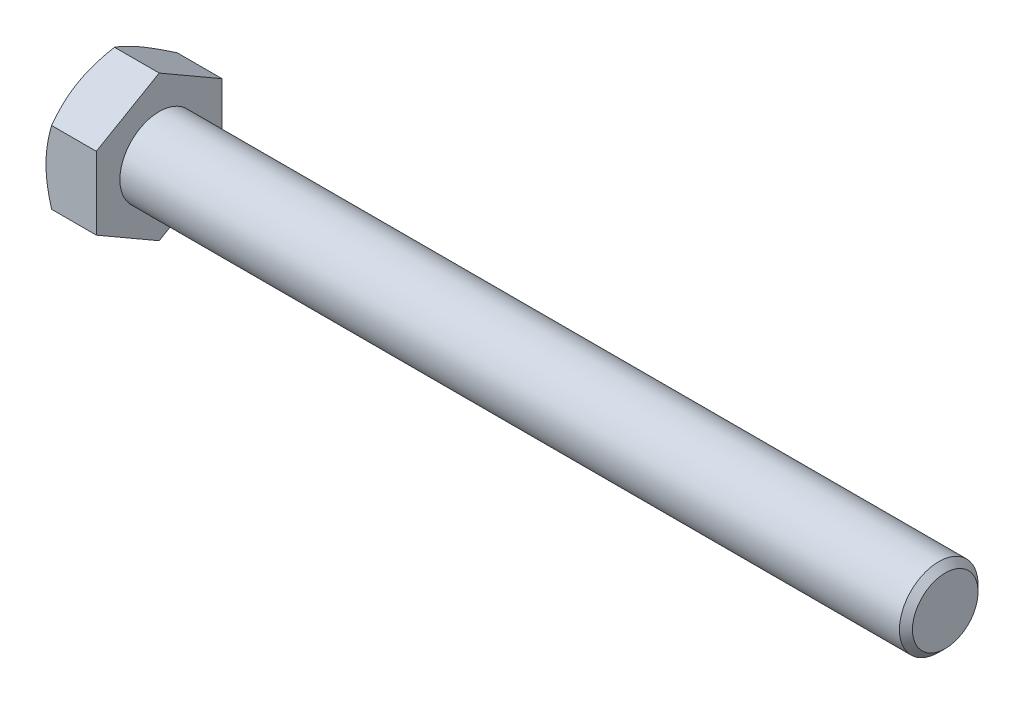
SolidWorks part; units mm, degrees
extrude "BaseHead" add sketch "Sketch1" along normal blind 6.4
sketch "Sketch1" plane through (0, 0, 0) normal (1, 0, 0) x (0, 0, -1)
  line L0 (8, 4.6188) -> (8, -4.6188)
  line L1 (-8, 4.6188) -> (-8, -4.6188)
  line L2 (8, -4.6188) -> (0, -9.2376)
  line L3 (0, -9.2376) -> (-8, -4.6188)
  line L4 (8, 4.6188) -> (0, 9.2376)
  line L5 (0, 9.2376) -> (-8, 4.6188)
  dimension "Width_flats" = 16
  dimension "D2" = 120
  dimension "D3" = 8
  dimension "D4" = 8
  dimension "D5" = 8
ref_plane "Plane1" through (0, 0, 0) normal (0, 0, 1) x (1, 0, 0)
ref_plane "Plane2" through (0, 0, 0) normal (0, 1, 0) x (1, 0, 0)
ref_plane "Plane3" through (0, 0, 0) normal (1, 0, 0) x (0, 0, -1)
sketch "BodySke" plane through (0, 0, 0) normal (0, 0, 1) x (1, 0, 0)
  line L1 (0, 0) -> (106.4, 0)
  line L2 (0, 0) -> (0, 5)
  line L4 (106.4, 0) -> (106.4, 4.172)
  line L5 (6.4, 9.2376) -> (6.4, 4.6188) construction
  line L6 (106.4, 4.172) -> (105.572, 5)
  line L7 (0, 0) -> (110.49, 0) construction
  line L8 (106.4, -4.172) -> (105.572, -5) construction
  line L9 (0, 4.6188) -> (0, -4.6188) construction
  line L10 (7.9, 15.24) -> (7.9, -1.27) construction
  line L11 (80.4, 15.24) -> (80.4, -1.27) construction
  line L12 (6.4, 4.6188) -> (6.4, -4.6188) construction
  line L15 (0, 5) -> (105.572, 5)
  dimension "Body_ch_ang" = 45
  dimension "Minor_dia" = 8.344
  dimension "Diameter" = 10
revolve "BaseBody" add sketch "BodySke" angle 360 about L7
cosmetic thread "ThreadCosmetic" parameters "Thread_length"=26, "Thread_minor"=8.344
fillet "HeadFillet" [suppressed] radius 0.4
sketch "Sketch3" plane through (0, 0, 0) normal (0, 0, 1) x (1, 0, 0)
  line L0 (0, 8) -> (3.6013, 14.2376)
  line L1 (0, 9.2376) -> (0, 4.6188) construction
  line L2 (3.6013, 14.2376) -> (3.6013, 19.2376)
  line L3 (3.6013, 19.2376) -> (-10, 19.2376)
  line L4 (-10, 19.2376) -> (-10, 8)
  line L5 (-10, 8) -> (0, 8)
  line L6 (0, 0) -> (99.06, 0) construction
  line L7 (6.4, 9.2376) -> (0, 9.2376) construction
  dimension "D1" = 8
  dimension "D2" = 5
  dimension "D3" = 10
  dimension "D4" = 5
  dimension "Head_ch_ang" = 30
revolve "HeadChamfer" cut sketch "Sketch3" angle 360 about L6
sketch "ThdSchSke" plane through (0, 0, 0) normal (0, 0, 1) x (1, 0, 0)
  line L0 (80.4, -4.172) -> (79.8202, -5)
  line L1 (80.4, -4.172) -> (80.9798, -5)
  line L2 (80.9798, -5) -> (80.9798, -6.25)
  line L3 (-3.175, 0) -> (5.1513, 0) construction
  line L5 (80.9798, -6.25) -> (79.8202, -6.25)
  line L6 (79.8202, -6.25) -> (79.8202, -5)
  dimension "Thread_minor" = 8.344
  dimension "Diameter" = 10
  dimension "Start" = 80.4
revolve "ThreadSchematic" [suppressed] cut sketch "ThdSchSke" angle 360 about L3
pattern_linear "ThdSchPat" [suppressed]
equation "\"D3@Sketch1\" = \"Width_flats@Sketch1\" / 2"
equation "\"D4@Sketch1\" = \"D3@Sketch1\""
equation "\"D5@Sketch1\" = \"D4@Sketch1\""
equation "\"Thread_minor@ThreadCosmetic\" = \"Minor_dia@BodySke\""
equation "\"D1@Sketch3\" = \"Width_flats@Sketch1\" / 2"
equation "\"Thread_length@ThreadCosmetic\" = ((sgn( (\"Length@BodySke\" - \"Advance@BodySke\" ) - \"Thread_nom@BodySke\" )-1)*( (\"Length@BodySke\" - \"Advance@BodySke\" ) - \"Thread_nom@BodySke\" ))/-2+ \"Thread_nom@BodySke\""
equation "\"Thread_minor@ThdSchSke\" = \"Minor_dia@BodySke\""
equation "\"Diameter@ThdSchSke\" = \"Diameter@BodySke\""
equation "\"Overcut@ThdSchSke\" = \"Diameter@BodySke\" * 1.25"
equation "\"Start@ThdSchSke\" = \"Head_ht@BaseHead\" + \"Length@BodySke\" - \"Thread_length@ThreadCosmetic\"  '---Non-countersunk---"
equation "\"Num_threads@ThdSchPat\" = int( \"Thread_length@ThreadCosmetic\" / \"Advance@BodySke\" + 0.999 )  + 1"
equation "\"Advance@ThdSchPat\" = \"Thread_length@ThreadCosmetic\" /  (\"Num_threads@ThdSchPat\" - 1) 'relax it"
equation "\"Num_threads@ThdSchPat\" = \"Num_threads@ThdSchPat\" - sgn( \"Num_threads@ThdSchPat\" - 1) '---chamfered tips only---"
